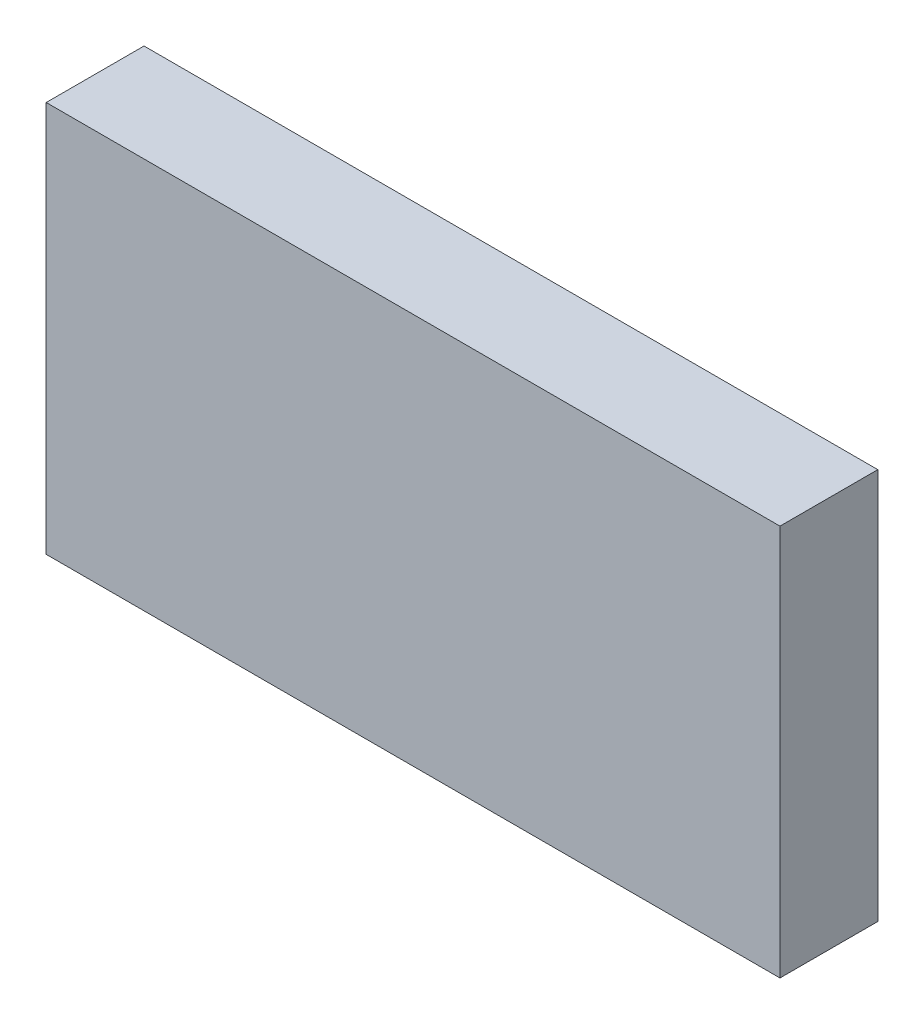
SolidWorks part; units mm, degrees
ref_plane "前视基准面" through (0, 0, 0) normal (0, 0, 1) x (1, 0, 0)
ref_plane "上视基准面" through (0, 0, 0) normal (0, 1, 0) x (1, 0, 0)
ref_plane "右视基准面" through (0, 0, 0) normal (1, 0, 0) x (0, 0, -1)
other "Configuration Table"
sketch "草图1" plane through (0, 0, 0) normal (0, 0, 1) x (1, 0, 0)
  line L0 (0, 0) -> (15, 0)
  line L1 (15, 0) -> (15, 8)
  line L2 (15, 8) -> (0, 8)
  line L3 (0, 8) -> (0, 0)
  dimension "width" = 15
  dimension "height" = 8
extrude "BlockExtrude" add sketch "草图1" along normal blind 2
